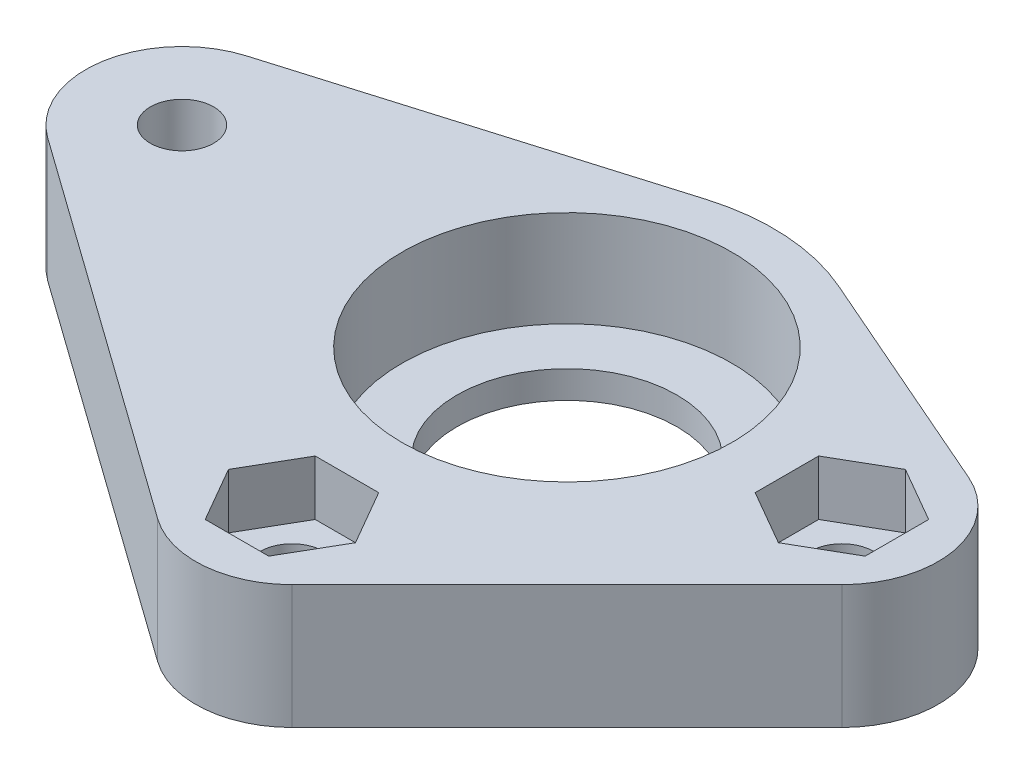
SolidWorks part; units mm, degrees
ref_plane "Front Plane" through (0, 0, 0) normal (0, 0, 1) x (1, 0, 0)
ref_plane "Top Plane" through (0, 0, 0) normal (0, 1, 0) x (1, 0, 0)
ref_plane "Right Plane" through (0, 0, 0) normal (1, 0, 0) x (0, 0, -1)
sketch "Sketch1" plane through (0, 0, 0) normal (0, 1, 0) x (1, 0, 0)
  line L0 (0, 0) -> (-14, 0) construction
  line L1 (0, 0) -> (10, 0) construction
  line L2 (3, 6.8739) -> (11.4, 3.2078)
  line L3 (12.4749, -2.4749) -> (2.4749, -12.4749)
  line L4 (-2.0343, -12.8481) -> (-16.0343, -2.8481)
  line L5 (-15, 3.3541) -> (-2.1429, 7.1874)
  circle A0 centre (0, 0) radius 4
  circle A1 centre (0, 0) radius 7.5 construction
  circle A2 centre (-14, 0) radius 1.15
  circle A3 centre (10, 0) radius 1.15
  circle A4 centre (0, -10) radius 1.15
  arc A5 (10, 0) -> (0, -10) centre (0, 0) cw construction
  circle A6 centre (10, 0) radius 3.5 construction
  circle A7 centre (0, -10) radius 3.5 construction
  circle A8 centre (-14, 0) radius 3.5 construction
  circle A9 centre (0, 0) radius 6 construction
  arc A10 (-2.1429, 7.1874) -> (3, 6.8739) centre (0, 0) cw
  arc A11 (11.4, 3.2078) -> (12.4749, -2.4749) centre (10, 0) cw
  arc A12 (2.4749, -12.4749) -> (-2.0343, -12.8481) centre (0, -10) cw
  arc A13 (-15, 3.3541) -> (-16.0343, -2.8481) centre (-14, 0) ccw
  dimension "D1" = 8
  dimension "D2" = 15
  dimension "D3" = 14
  dimension "D4" = 10
  dimension "D5" = 2.3
  dimension "D6" = 7
  dimension "D7" = 12
extrude "Boss-Extrude1" add sketch "Sketch1" along normal blind 4.5
sketch "Sketch2" plane through (0, 4.5, 0) normal (0, 1, 0) x (1, 0, 0)
  circle A0 centre (0, 0) radius 6
  dimension "D1" = 12
extrude "Cut-Extrude1" cut sketch "Sketch2" against normal blind 3.5
sketch "Sketch3" plane through (0, 4.5, 0) normal (0, 1, 0) x (1, 0, 0)
  line L1 (12, -1.1547) -> (12, 1.1547)
  line L2 (12, 1.1547) -> (10, 2.3094)
  line L3 (10, 2.3094) -> (8, 1.1547)
  line L4 (8, 1.1547) -> (8, -1.1547)
  line L5 (8, -1.1547) -> (10, -2.3094)
  line L6 (10, -2.3094) -> (12, -1.1547)
  line L7 (2.3094, -10) -> (1.1547, -8)
  line L8 (1.1547, -8) -> (-1.1547, -8)
  line L9 (-1.1547, -8) -> (-2.3094, -10)
  line L10 (-2.3094, -10) -> (-1.1547, -12)
  line L11 (-1.1547, -12) -> (1.1547, -12)
  line L12 (1.1547, -12) -> (2.3094, -10)
  circle A1 centre (10, 0) radius 2 construction
  circle A2 centre (0, -10) radius 2 construction
  dimension "D1" = 4
  dimension "D2" = 4
extrude "Cut-Extrude2" cut sketch "Sketch3" against normal blind 2
sketch "Sketch4" plane through (0, 0, 0) normal (0, -1, 0) x (1, 0, 0)
  line L1 (-12, -1.1547) -> (-12, 1.1547)
  line L2 (-12, 1.1547) -> (-14, 2.3094)
  line L3 (-14, 2.3094) -> (-16, 1.1547)
  line L4 (-16, 1.1547) -> (-16, -1.1547)
  line L5 (-16, -1.1547) -> (-14, -2.3094)
  line L6 (-14, -2.3094) -> (-12, -1.1547)
  circle A0 centre (-14, 0) radius 2 construction
  dimension "D1" = 4
extrude "Cut-Extrude3" cut sketch "Sketch4" against normal blind 2
